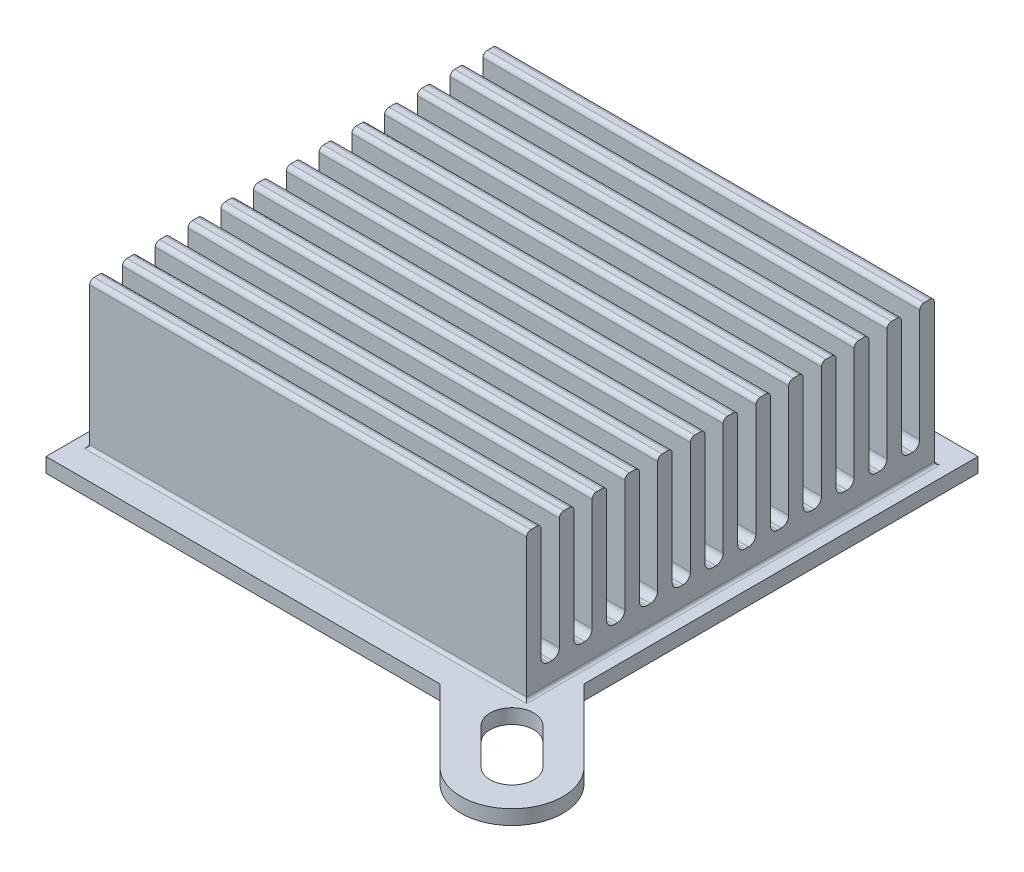
SolidWorks part; units mm, degrees
ref_plane "Płaszczyzna przednia" through (0, 0, 0) normal (0, 0, 1) x (1, 0, 0)
ref_plane "Płaszczyzna górna" through (0, 0, 0) normal (0, 1, 0) x (1, 0, 0)
ref_plane "Płaszczyzna prawa" through (0, 0, 0) normal (1, 0, 0) x (0, 0, -1)
sketch "Szkic1" plane through (0, 0, 0) normal (0, 1, 0) x (1, 0, 0)
  line L0 (-16, 20.9497) -> (20.9497, -16)
  line L5 (-16, -16) -> (16, -16)
  line L6 (-16, -16) -> (-16, 16)
  line L7 (-16, 16) -> (16, 16)
  line L8 (16, -16) -> (16, 16)
  line L9 (-16, -16) -> (16, 16) construction
  line L10 (-16, 16) -> (16, -16) construction
  line L11 (-16, 20.9497) -> (-20.9497, 16)
  line L12 (20.9497, -16) -> (16, -20.9497)
  line L13 (-20.9497, 16) -> (16, -20.9497)
  circle A0 centre (-18.4749, 18.4749) radius 3.5
  circle A1 centre (18.4749, -18.4749) radius 3.5
  point P0 (0, 0)
  point P10 (12.8599, -23.5324)
  point P13 (16, -20.9497)
  point P16 (0, 0)
  dimension "D3" = 7
  dimension "D4" = 7
  dimension "D1" = 32
  dimension "D2" = 32
extrude "Dodanie-wyciągnięcie2" add sketch "Szkic1" along normal blind 1 contours L11 A0 | A0 L11 | A0 L7 L0 | L6 L13 L5 L8 L0 L7 | A0 L13 L6 | L13 L6 L5 | L0 L8 L7 | A1 L0 L8 | L12 A1 | A1 L5 L13 | L12 A1
sketch "Szkic2" plane through (0, 1, 0) normal (0, 1, 0) x (1, 0, 0)
  line L0 (-18.4749, 18.4749) -> (-16, 16) construction
  line L1 (-17.4142, 19.5355) -> (-14.9393, 17.0607)
  line L2 (-19.5355, 17.4142) -> (-17.0607, 14.9393)
  line L3 (-16, 20.9497) -> (-11.0503, 16) construction
  line L4 (-20.9497, 16) -> (-16, 11.0503) construction
  line L5 (-16, -16) -> (-16, 11.0503) construction
  line L6 (-16, -16) -> (16, 16) construction
  line L7 (18.4749, -18.4749) -> (16, -16) construction
  line L8 (19.5355, -17.4142) -> (17.0607, -14.9393)
  line L9 (17.4142, -19.5355) -> (14.9393, -17.0607)
  arc A0 (-17.4142, 19.5355) -> (-19.5355, 17.4142) centre (-18.4749, 18.4749) ccw
  arc A1 (-17.0607, 14.9393) -> (-14.9393, 17.0607) centre (-16, 16) ccw
  arc A2 (-16, 20.9497) -> (-20.9497, 16) centre (-18.4749, 18.4749) ccw construction
  arc A3 (19.5355, -17.4142) -> (17.4142, -19.5355) centre (18.4749, -18.4749) cw
  arc A4 (14.9393, -17.0607) -> (17.0607, -14.9393) centre (16, -16) cw
  point P2 (-17.2374, 17.2374)
  point P22 (17.2374, -17.2374)
  dimension "D1" = 2
  dimension "D2" = 2
  dimension "D3" = 0
extrude "Wytnij-wyciągnięcie1" cut sketch "Szkic2" against normal through all
sketch "Szkic3" plane through (0, 1, 0) normal (0, 1, 0) x (1, 0, 0)
  line L0 (16, -11.0503) -> (16, 16) construction
  line L1 (-15, 13) -> (15, 13)
  line L2 (-15, 13) -> (-15, 14)
  line L3 (-15, 14) -> (15, 14)
  line L4 (15, 13) -> (15, 14)
  line L6 (-11.0503, 16) -> (16, 16) construction
  line L7 (-15, 11.75) -> (15, 11.75)
  line L8 (-15, 10.75) -> (15, 10.75)
  line L9 (-15, 10.75) -> (-15, 11.75)
  line L10 (15, 10.75) -> (15, 11.75)
  line L11 (-15, 9.5) -> (15, 9.5)
  line L12 (-15, 8.5) -> (15, 8.5)
  line L13 (-15, 8.5) -> (-15, 9.5)
  line L14 (15, 8.5) -> (15, 9.5)
  line L15 (-15, 7.25) -> (15, 7.25)
  line L16 (-15, 6.25) -> (15, 6.25)
  line L17 (-15, 6.25) -> (-15, 7.25)
  line L18 (15, 6.25) -> (15, 7.25)
  line L19 (-15, 5) -> (15, 5)
  line L20 (-15, 4) -> (15, 4)
  line L21 (-15, 4) -> (-15, 5)
  line L22 (15, 4) -> (15, 5)
  line L23 (-15, 2.75) -> (15, 2.75)
  line L24 (-15, 1.75) -> (15, 1.75)
  line L25 (-15, 1.75) -> (-15, 2.75)
  line L26 (15, 1.75) -> (15, 2.75)
  line L27 (-15, 0.5) -> (15, 0.5)
  line L28 (-15, -0.5) -> (15, -0.5)
  line L29 (-15, -0.5) -> (-15, 0.5)
  line L30 (15, -0.5) -> (15, 0.5)
  line L31 (-15, -1.75) -> (15, -1.75)
  line L32 (-15, -2.75) -> (15, -2.75)
  line L33 (-15, -2.75) -> (-15, -1.75)
  line L34 (15, -2.75) -> (15, -1.75)
  line L35 (-15, -4) -> (15, -4)
  line L36 (-15, -5) -> (15, -5)
  line L37 (-15, -5) -> (-15, -4)
  line L38 (15, -5) -> (15, -4)
  line L39 (-15, -6.25) -> (15, -6.25)
  line L40 (-15, -7.25) -> (15, -7.25)
  line L41 (-15, -7.25) -> (-15, -6.25)
  line L42 (15, -7.25) -> (15, -6.25)
  line L43 (-15, -8.5) -> (15, -8.5)
  line L44 (-15, -9.5) -> (15, -9.5)
  line L45 (-15, -9.5) -> (-15, -8.5)
  line L46 (15, -9.5) -> (15, -8.5)
  line L47 (-15, -10.75) -> (15, -10.75)
  line L48 (-15, -11.75) -> (15, -11.75)
  line L49 (-15, -11.75) -> (-15, -10.75)
  line L50 (15, -11.75) -> (15, -10.75)
  line L51 (-15, -13) -> (15, -13)
  line L52 (-15, -14) -> (15, -14)
  line L53 (-15, -14) -> (-15, -13)
  line L54 (15, -14) -> (15, -13)
  line L56 (-16, -16) -> (11.0503, -16) construction
  line L58 (-15, 14) -> (15, 14)
  line L60 (-15, -14) -> (15, -14)
  point P58 (15, -14)
  dimension "D1" = 1
  dimension "D2" = 30
  dimension "D3" = 1
  dimension "D4" = 2
  dimension "D6" = 2
  dimension "D5" = 13
sketch "Szkic4" plane through (0, 1, 0) normal (0, 1, 0) x (1, 0, 0)
  line L1 (-15, 14) -> (15, 14)
  line L2 (-15, 14) -> (-15, -14)
  line L3 (-15, -14) -> (15, -14)
  line L4 (15, 14) -> (15, -14)
extrude "Dodanie-wyciągnięcie3" add sketch "Szkic4" along normal blind 1.5
extrude "Dodanie-wyciągnięcie4" add sketch "Szkic3" along normal blind 10 contours L1 L4 L3 L2 | L20 L22 L19 L21 | L36 L38 L35 L37 | L48 L50 L47 L49 | L52 L54 L51 L53 | L7 L10 L8 L9 | L11 L14 L12 L13 | L15 L18 L16 L17 | L23 L26 L24 L25 | L27 L30 L28 L29 | L31 L34 L32 L33 | L39 L42 L40 L41 | L43 L46 L44 L45
fillet "Zaokrąglenie1" radius 0.3 26 edges at (0, 11, 14) (0, 11, 9.5) (0, 11, 8.5) (0, 11, 7.25) (0, 11, 6.25) (0, 11, 2.75) (0, 11, 13) (0, 11, 10.75) (0, 11, 11.75) (0, 11, 4) (0, 11, 5) (0, 11, 1.75) (0, 11, -0.5) (0, 11, 0.5) (0, 11, -1.75) (0, 11, -2.75) (0, 11, -4) (0, 11, -5) (0, 11, -6.25) (0, 11, -7.25) (0, 11, -8.5) (0, 11, -9.5) (0, 11, -10.75) (0, 11, -11.75) (0, 11, -13) (0, 11, -14)
fillet "Zaokrąglenie2" radius 0.5 24 edges at (0, 2.5, 13) (0, 2.5, 11.75) (0, 2.5, 10.75) (0, 2.5, 9.5) (0, 2.5, 8.5) (0, 2.5, 7.25) (0, 2.5, 6.25) (0, 2.5, 5) (0, 2.5, 4) (0, 2.5, 2.75) (0, 2.5, 1.75) (0, 2.5, 0.5) (0, 2.5, -0.5) (0, 2.5, -1.75) (0, 2.5, -2.75) (0, 2.5, -4) (0, 2.5, -5) (0, 2.5, -6.25) (0, 2.5, -7.25) (0, 2.5, -8.5) (0, 2.5, -9.5) (0, 2.5, -10.75) (0, 2.5, -11.75) (0, 2.5, -13)
fillet "Zaokrąglenie3" radius 0.2 4 edges at (15, 1, 0) (0, 1, -14) (0, 1, 14) (-15, 1, 0)
equation "\"D2@Szkic1\"=\"D1@Szkic1\""
equation "\"D4@Szkic1\"=\"D3@Szkic1\""
equation "\"D2@Szkic2\"=\"D1@Szkic2\""
equation "\"D6@Szkic3\"=\"D4@Szkic3\""
